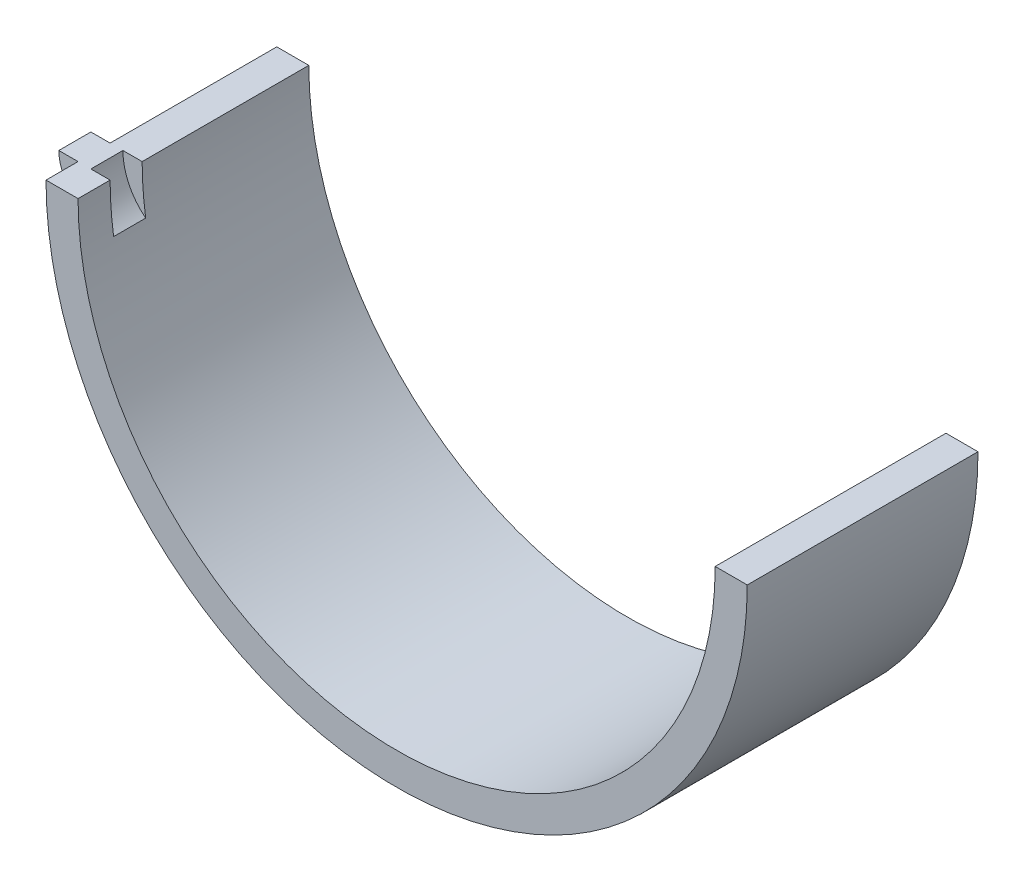
SolidWorks part; units mm, degrees
material "201 Annealed Stainless Steel (SS)"
ref_plane "Front Plane" through (0, 0, 0) normal (0, 0, 1) x (1, 0, 0)
ref_plane "Top Plane" through (0, 0, 0) normal (0, 1, 0) x (1, 0, 0)
ref_plane "Right Plane" through (0, 0, 0) normal (1, 0, 0) x (0, 0, -1)
sketch "Sketch1" plane through (0, 0, 0) normal (0, 0, 1) x (1, 0, 0)
  line L0 (0, 0) -> (-54.6361, 0) construction
  line L1 (-13.8938, 13.8938) -> (13.8938, 13.8938) construction
  line L2 (13.8938, 13.8938) -> (12.6238, 13.8938)
  line L3 (-13.8938, 13.8938) -> (-12.6238, 13.8938)
  circle A0 centre (0, 13.8938) radius 13.8938 construction
  circle A1 centre (0, 13.8938) radius 12.6238 construction
  arc A2 (-12.6238, 13.8938) -> (12.6238, 13.8938) centre (0, 13.8938) ccw
  arc A3 (13.8938, 13.8938) -> (-13.8938, 13.8938) centre (0, 13.8938) cw
  dimension "D1" = 54.6361
  dimension "D2" = 1.27
  dimension "D3" = 25.2476
extrude "Boss-Extrude1" add sketch "Sketch1" against normal blind 9.144
sketch "Sketch2" plane through (0, 0, 0) normal (0, 1, 0) x (1, 0, 0)
  line L0 (13.8938, 0) -> (-13.8938, 9.144) construction
  circle A0 centre (0, 4.572) radius 1.27
  dimension "D1" = 2.54
extrude "Cut-Extrude1" [suppressed] cut sketch "Sketch2" along normal up to next
ref_plane "Plane1" through (0, 0, -1.27) normal (0, 0, 1) x (1, 0, 0)
sketch "Sketch3" plane through (0, 0, -1.27) normal (0, 0, 1) x (1, 0, 0)
  line L0 (12.6238, 13.8938) -> (-12.6238, 13.8938) construction
  line L1 (13.8938, 13.8938) -> (14.6558, 13.8938) construction
  line L2 (14.6558, 13.8938) -> (14.6558, 15.8611) construction
  line L3 (0, 13.8938) -> (0, 1.27) construction
  line L4 (-13.8938, 13.8938) -> (-14.6558, 13.8938)
  arc A0 (13.8938, 13.8938) -> (13.8236, 12.499) centre (0, 13.8938) cw construction
  arc A1 (13.8236, 12.499) -> (14.6558, 13.8938) centre (13.0708, 13.8938) ccw construction
  arc A2 (-12.6238, 13.8938) -> (12.6238, 13.8938) centre (0, 13.8938) ccw construction
  arc A3 (-13.8236, 12.499) -> (-14.6558, 13.8938) centre (-13.0708, 13.8938) cw
  arc A4 (-13.8938, 13.8938) -> (-13.8236, 12.499) centre (0, 13.8938) ccw
  dimension "D1" = 1.9673
  dimension "D2" = 0.762
extrude "Boss-Extrude2" add sketch "Sketch3" against normal blind 1.27
sketch "Sketch4" plane through (0, 0, -1.27) normal (0, 0, 1) x (1, 0, 0)
  line L0 (12.6238, 13.8938) -> (-12.6238, 13.8938) construction
  line L1 (13.3858, 13.8938) -> (12.6238, 13.8938)
  line L2 (13.8938, 13.8938) -> (12.6238, 13.8938) construction
  line L4 (13.3858, 13.8938) -> (13.3858, 15.3845) construction
  line L5 (15.048, 12.0234) -> (12.4845, 12.0234) construction
  line L6 (0, 13.8938) -> (0, 1.27) construction
  line L7 (-13.3858, 13.8938) -> (-12.6238, 13.8938)
  arc A0 (12.6238, 13.8938) -> (12.4845, 12.0234) centre (0, 13.8938) cw construction
  arc A1 (13.3858, 13.8938) -> (12.4845, 12.0234) centre (10.9944, 13.8938) cw construction
  arc A2 (-12.6238, 13.8938) -> (12.6238, 13.8938) centre (0, 13.8938) ccw construction
  arc A3 (-13.3858, 13.8938) -> (-12.4845, 12.0234) centre (-10.9944, 13.8938) ccw
  arc A4 (-12.6238, 13.8938) -> (-12.4845, 12.0234) centre (0, 13.8938) ccw
  dimension "D1" = 1.4907
extrude "Cut-Extrude2" cut sketch "Sketch4" against normal blind 1.27 contours A3 A4 L7
